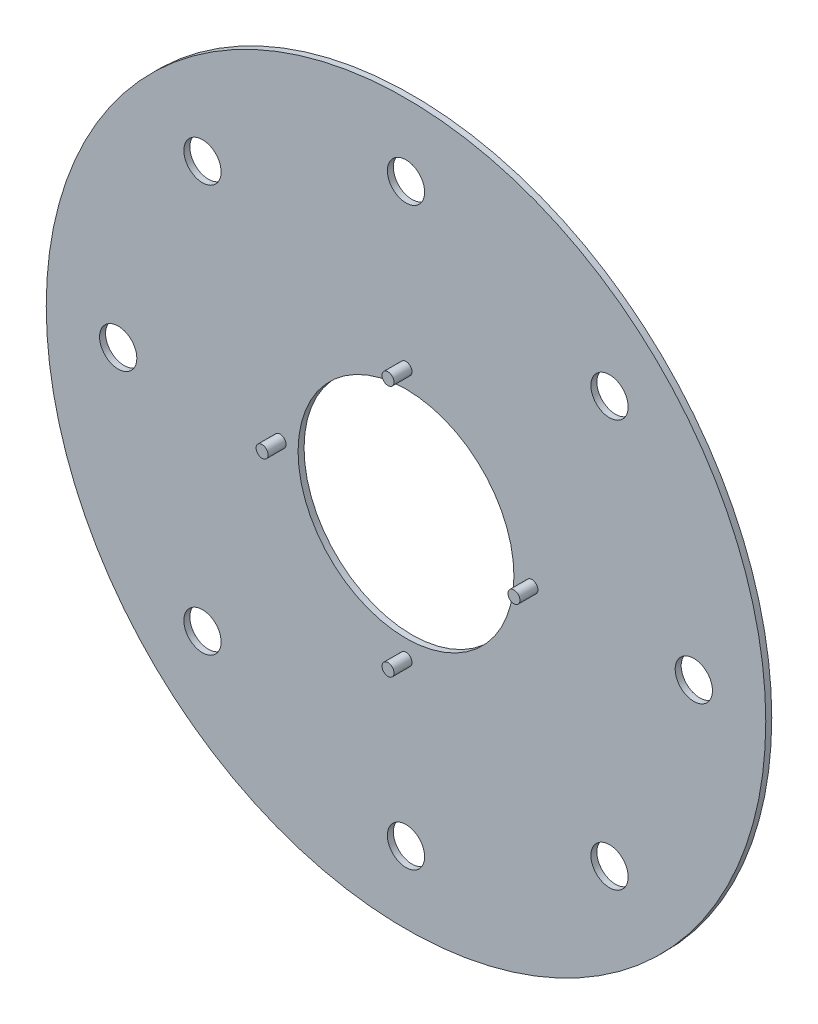
SolidWorks part; units mm, degrees
ref_plane "Front Plane" through (0, 0, 0) normal (0, 0, 1) x (1, 0, 0)
ref_plane "Top Plane" through (0, 0, 0) normal (0, 1, 0) x (1, 0, 0)
ref_plane "Right Plane" through (0, 0, 0) normal (1, 0, 0) x (0, 0, -1)
sketch "Sketch1" plane through (0, 0, 0) normal (0, 0, 1) x (1, 0, 0)
  circle A0 centre (0, 0) radius 12.7
  circle A1 centre (0, 0) radius 60
  circle A2 centre (0, 48) radius 3.1072
  circle A3 centre (33.9411, 33.9411) radius 3.1072
  circle A4 centre (48, 0) radius 3.1072
  circle A5 centre (33.9411, -33.9411) radius 3.1072
  circle A6 centre (0, -48) radius 3.1072
  circle A7 centre (-33.9411, -33.9411) radius 3.1072
  circle A8 centre (-48, 0) radius 3.1072
  circle A9 centre (-33.9411, 33.9411) radius 3.1072
  point P22 (0, 0)
  dimension "D1" = 48
  dimension "D2" = 120
  dimension "D4" = 25.4
  dimension "D3" = 8
extrude "Boss-Extrude4" add sketch "Sketch1" along normal blind 1
sketch "Sketch4" plane through (0, 0, 1) normal (0, 0, 1) x (1, 0, 0)
  line L0 (0, 0) -> (0, 41.8032) construction
  circle A0 centre (0, 21) radius 1
  circle A2 centre (21, 0) radius 1
  circle A3 centre (0, -21) radius 1
  circle A4 centre (-21, 0) radius 1
  point P14 (0, 0)
  dimension "D1" = 21
  dimension "D2" = 0
  dimension "D3" = 4
extrude "Boss-Extrude5" add sketch "Sketch4" along normal blind 3
sketch "Sketch5" plane through (0, 0, 1) normal (0, 0, 1) x (1, 0, 0)
  circle A0 centre (0, 0) radius 18
extrude "Cut-Extrude1" cut sketch "Sketch5" against normal blind 3
